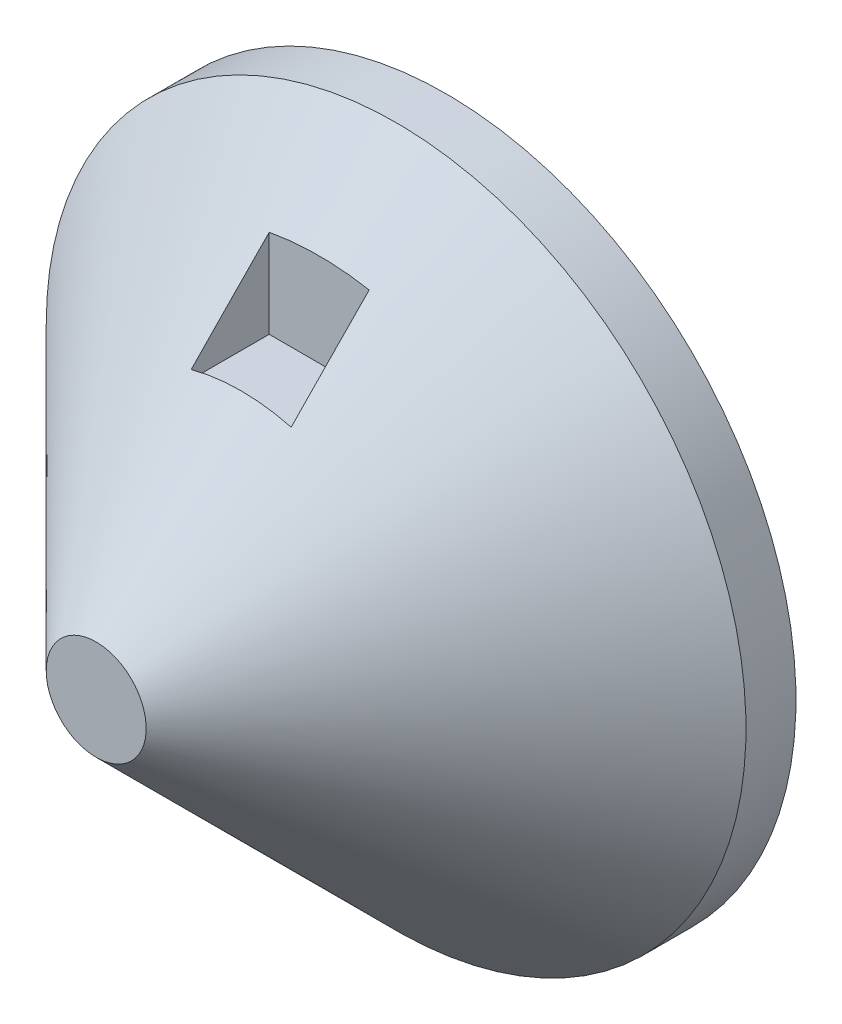
SolidWorks part; units mm, degrees
ref_plane "Front Plane" through (0, 0, 0) normal (0, 0, 1) x (1, 0, 0)
ref_plane "Top Plane" through (0, 0, 0) normal (0, 1, 0) x (1, 0, 0)
ref_plane "Right Plane" through (0, 0, 0) normal (1, 0, 0) x (0, 0, -1)
sketch "Sketch2" plane through (0, 0, 0) normal (1, 0, 0) x (0, 0, -1)
  line L0 (0, 0) -> (0, 6.35)
  line L1 (0, 55) -> (0, -55) construction
  line L2 (0, 0) -> (38.1, 0) construction
  line L3 (55, 0) -> (-55, 0) construction
  line L4 (6.35, 0) -> (44.45, 0) construction
  line L7 (38.1, 44.45) -> (0, 6.35)
  line L8 (0, 0) -> (6.35, 0) construction
  line L9 (38.1, 44.45) -> (44.45, 44.45)
  line L10 (44.45, 44.45) -> (44.45, 38.1)
  line L11 (44.45, 38.1) -> (6.35, 0)
  line L12 (6.35, 0) -> (0, 0)
  line L13 (44.45, 0) -> (44.45, 38.1) construction
  point P11 (38.1, 0)
  dimension "D1" = 6.35
  dimension "D4" = 6.35
  dimension "D5" = 6.35
  dimension "D6" = 6.35
revolve "Revolve2" add sketch "Sketch2" angle 360 about L12
sketch "Sketch4" plane through (0, 0, 0) normal (0, 1, 0) x (1, 0, 0)
  line L0 (0, 0) -> (0, 44.45) construction
  line L1 (0, -24.4475) -> (0, 24.4475) construction
  line L3 (-6.35, 18.4201) -> (6.35, 18.4201)
  line L4 (-6.35, 18.4201) -> (-6.35, 28.3261)
  line L5 (-6.35, 28.3261) -> (6.35, 28.3261)
  line L6 (6.35, 18.4201) -> (6.35, 28.3261)
  line L7 (-6.35, 18.4201) -> (6.35, 28.3261) construction
  line L8 (-6.35, 28.3261) -> (6.35, 18.4201) construction
  point P5 (0, 23.3731)
  dimension "D1" = 44.45
  dimension "D2" = 9.906
  dimension "D3" = 12.7
extrude "Cut-Extrude1" cut sketch "Sketch4" against normal blind 15.24 from offset 38.1
